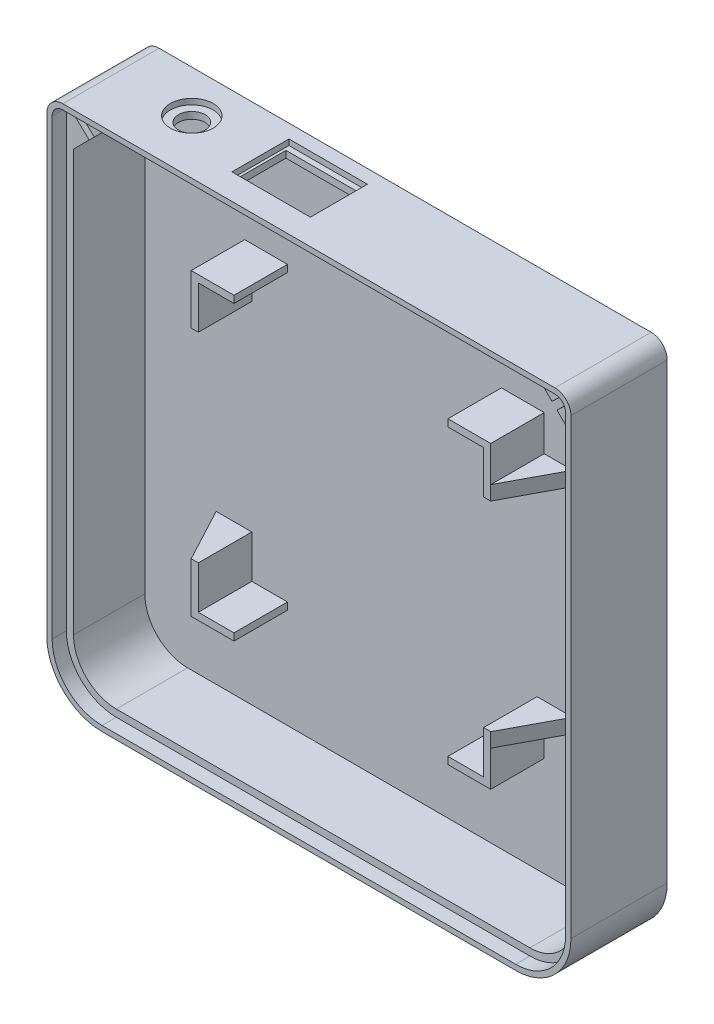
SolidWorks part; units mm, degrees
ref_plane "Front Plane" through (0, 0, 0) normal (0, 0, 1) x (1, 0, 0)
ref_plane "Top Plane" through (0, 0, 0) normal (0, 1, 0) x (1, 0, 0)
ref_plane "Right Plane" through (0, 0, 0) normal (1, 0, 0) x (0, 0, -1)
sketch "Sketch1" plane through (0, 0, 0) normal (0, 0, 1) x (1, 0, 0)
  line L1 (58, -72) -> (-58, -72)
  line L2 (72, -58) -> (72, 72)
  line L3 (72, 72) -> (-72, 72)
  line L4 (-72, -58) -> (-72, 72)
  line L5 (72, -72) -> (-72, 72) construction
  line L6 (72, 72) -> (-72, -72) construction
  arc A0 (58, -72) -> (72, -58) centre (58, -58) ccw
  arc A1 (-58, -72) -> (-72, -58) centre (-58, -58) cw
  point P0 (0, 0)
  dimension "D3" = 14
  dimension "D1" = 144
  dimension "D2" = 144
extrude "Boss-Extrude1" add sketch "Sketch1" along normal blind 3
sketch "Sketch2" plane through (0, 0, 3) normal (0, 0, 1) x (1, 0, 0)
  line L4 (-70, 70) -> (-70, -58)
  line L5 (-58, -70) -> (58, -70)
  line L6 (70, -58) -> (70, 70)
  line L7 (70, 70) -> (-70, 70)
  line L8 (-72, 72) -> (-72, -58)
  line L9 (-58, -72) -> (58, -72)
  line L10 (72, -58) -> (72, 72)
  line L11 (72, 72) -> (-72, 72)
  line L12 (-72, 72) -> (-72, -58)
  line L13 (-58, -72) -> (58, -72)
  line L14 (72, -58) -> (72, 72)
  line L15 (72, 72) -> (-72, 72)
  arc A2 (-70, -58) -> (-58, -70) centre (-58, -58) ccw
  arc A3 (58, -70) -> (70, -58) centre (58, -58) ccw
  arc A4 (-72, -58) -> (-58, -72) centre (-58, -58) ccw
  arc A5 (58, -72) -> (72, -58) centre (58, -58) ccw
  arc A6 (-72, -58) -> (-58, -72) centre (-58, -58) ccw
  arc A7 (58, -72) -> (72, -58) centre (58, -58) ccw
  dimension "D1" = 0
  dimension "D2" = 2
extrude "Boss-Extrude2" add sketch "Sketch2" along normal blind 20
chamfer "Chamfer1" distance 10 angle 45 2 edges at (70, 70, 13) (-70, 70, 13)
sketch "Sketch3" plane through (0, 0, 3) normal (0, 0, 1) x (1, 0, 0)
  line L0 (-42, -42) -> (-42, 42)
  line L1 (-40, -40) -> (40, -40)
  line L2 (-40, -40) -> (-40, 40)
  line L3 (-40, 40) -> (40, 40)
  line L4 (40, -40) -> (40, 40)
  line L5 (-40, -40) -> (40, 40) construction
  line L6 (-40, 40) -> (40, -40) construction
  line L7 (-42, 42) -> (42, 42)
  line L8 (42, -42) -> (42, 42)
  line L9 (-42, -42) -> (42, -42)
  point P0 (0, 0)
  dimension "D1" = 80
  dimension "D2" = 80
  dimension "D3" = 2
extrude "Boss-Extrude3" add sketch "Sketch3" along normal blind 15
ref_plane "Plane1" through (0, 20, 0) normal (0, 1, 0) x (1, 0, 0)
ref_plane "Plane2" through (0, -20, 0) normal (0, 1, 0) x (1, 0, 0)
sketch "Sketch6" plane through (0, -42, 0) normal (0, -1, 0) x (1, 0, 0)
  line L0 (-42, 3) -> (-50, 3)
  line L1 (-50, 3) -> (-42, 18)
  line L2 (-42, 18) -> (-42, 3)
  line L3 (0, 0) -> (0, 10.5) construction
  line L4 (42, 18) -> (42, 3)
  line L5 (50, 3) -> (42, 18)
  line L6 (42, 3) -> (50, 3)
extrude "Boss-Extrude4" add sketch "Sketch6" against normal blind 84
sketch "Sketch7" plane through (0, 0, 3) normal (0, 0, 1) x (1, 0, 0)
  line L0 (-50, 42) -> (-50, -42) construction
  line L1 (-50, 32) -> (-42, 32)
  line L2 (-50, 32) -> (-50, 42)
  line L3 (-50, 42) -> (-42, 42)
  line L4 (-42, 32) -> (-42, 42)
  line L5 (-42, 42) -> (-42, -42) construction
  line L6 (-42, 28) -> (-50, 28)
  line L7 (-42, 28) -> (-42, -28)
  line L8 (-42, -28) -> (-50, -28)
  line L9 (-50, 28) -> (-50, -28)
  line L10 (-50, -42) -> (50, -42) construction
  line L11 (-50, -32) -> (-42, -32)
  line L12 (-50, -32) -> (-50, -42)
  line L13 (-50, -42) -> (-42, -42)
  line L14 (-42, -32) -> (-42, -42)
  line L15 (-42, -42) -> (-50, -42) construction
  line L16 (0, 0) -> (0, 12.3491) construction
  line L17 (42, -32) -> (42, -42)
  line L18 (50, -42) -> (42, -42)
  line L19 (50, -32) -> (50, -42)
  line L20 (50, -32) -> (42, -32)
  line L21 (50, 28) -> (50, -28)
  line L22 (42, -28) -> (50, -28)
  line L23 (42, 28) -> (42, -28)
  line L24 (42, 28) -> (50, 28)
  line L25 (42, 32) -> (42, 42)
  line L26 (50, 42) -> (42, 42)
  line L27 (50, 32) -> (50, 42)
  line L28 (50, 32) -> (42, 32)
  line L29 (50, 42) -> (-50, 42) construction
  line L30 (-30, 42) -> (30, 42)
  line L31 (-30, 42) -> (-30, -42)
  line L32 (-30, -42) -> (30, -42)
  line L33 (30, 42) -> (30, -42)
  line L34 (-40, 40) -> (-40, -40) construction
  dimension "D1" = 10
  dimension "D2" = 4
  dimension "D3" = 4
  dimension "D4" = 10
  dimension "D5" = 60
  dimension "D6" = 10
extrude "Cut-Extrude1" cut sketch "Sketch7" along normal blind 72
fillet "Fillet1" radius 3 2 edges at (-72, 72, 11.5) (72, 72, 11.5)
sketch "Sketch9" plane through (0, 0, 0) normal (0, 0, -1) x (-1, 0, 0)
  line L1 (-72, -58) -> (72, -58) construction
  line L6 (72, -58) -> (72, 69)
  line L7 (69, 72) -> (-69, 72)
  line L8 (-72, 69) -> (-72, -58)
  line L9 (-58, -72) -> (58, -72)
  line L10 (73.5, -58) -> (73.5, 69)
  line L11 (69, 73.5) -> (-69, 73.5)
  line L12 (-73.5, 69) -> (-73.5, -58)
  line L13 (-58, -73.5) -> (58, -73.5)
  line L14 (73.5, -58) -> (73.5, 69)
  line L15 (69, 73.5) -> (-69, 73.5)
  line L16 (-73.5, 69) -> (-73.5, -58)
  line L17 (-58, -73.5) -> (58, -73.5)
  arc A4 (72, 69) -> (69, 72) centre (69, 69) ccw
  arc A5 (-69, 72) -> (-72, 69) centre (-69, 69) ccw
  arc A6 (-72, -58) -> (-58, -72) centre (-58, -58) ccw
  arc A7 (58, -72) -> (72, -58) centre (58, -58) ccw
  arc A8 (73.5, 69) -> (69, 73.5) centre (69, 69) ccw
  arc A9 (-69, 73.5) -> (-73.5, 69) centre (-69, 69) ccw
  arc A10 (-73.5, -58) -> (-58, -73.5) centre (-58, -58) ccw
  arc A11 (58, -73.5) -> (73.5, -58) centre (58, -58) ccw
  arc A12 (73.5, 69) -> (69, 73.5) centre (69, 69) ccw
  arc A13 (-69, 73.5) -> (-73.5, 69) centre (-69, 69) ccw
  arc A14 (-73.5, -58) -> (-58, -73.5) centre (-58, -58) ccw
  arc A15 (58, -73.5) -> (73.5, -58) centre (58, -58) ccw
  dimension "D1" = 1.5
  dimension "D2" = 1.5
extrude "Boss-Extrude5" add sketch "Sketch9" against normal blind 27
sketch "Sketch10" plane through (0, 70, 0) normal (0, -1, 0) x (1, 0, 0)
  line L0 (-58, 23) -> (-58, 3) construction
  circle A0 centre (-48, 11.8327) radius 3.75
  dimension "D1" = 10
extrude "Cut-Extrude2" cut sketch "Sketch10" against normal blind 26
sketch "Sketch11" plane through (0, 0, 23) normal (0, 0, 1) x (1, 0, 0)
  line L0 (-69.6886, 68.2749) -> (-65.604, 64.396)
  line L1 (-70, 60) -> (-60, 70) construction
  line L2 (-68.2424, 69.6527) -> (-64.1789, 65.8211)
  line L3 (-64.1789, 65.8211) -> (-65.604, 64.396)
  line L4 (0, 0) -> (0, 11.8359) construction
  line L5 (64.1789, 65.8211) -> (65.604, 64.396)
  line L6 (68.2424, 69.6527) -> (64.1789, 65.8211)
  line L7 (69.6886, 68.2749) -> (65.604, 64.396)
  arc A0 (-68.2424, 69.6527) -> (-69.6886, 68.2749) centre (-69, 69) ccw
  arc A1 (68.2424, 69.6527) -> (69.6886, 68.2749) centre (69, 69) cw
extrude "Cut-Extrude3" cut sketch "Sketch11" against normal blind 5
sketch "Sketch12" plane through (0, 0, 18) normal (0, 0, 1) x (1, 0, 0)
  line L0 (0, 0) -> (0, 13.3943) construction
  circle A0 centre (-69, 69) radius 1
  circle A1 centre (69, 69) radius 1
  point P8 (0, 0)
extrude "Cut-Extrude4" cut sketch "Sketch12" against normal blind 33 contours A1 | A0
sketch "Sketch14" plane through (0, 73.5, 0) normal (0, 1, 0) x (1, 0, 0)
  circle A0 centre (-48, -11.8327) radius 6
extrude "Cut-Extrude5" cut sketch "Sketch14" against normal blind 1.6
sketch "Sketch15" plane through (0, 73.5, 0) normal (0, 1, 0) x (1, 0, 0)
  line L1 (-28, -18.2327) -> (-7.5, -18.2327)
  line L2 (-28, -18.2327) -> (-28, -5.4327)
  line L3 (-28, -5.4327) -> (-7.5, -5.4327)
  line L4 (-7.5, -18.2327) -> (-7.5, -5.4327)
  line L5 (-28, -18.2327) -> (-7.5, -5.4327) construction
  line L6 (-28, -5.4327) -> (-7.5, -18.2327) construction
  circle A0 centre (-48, -11.8327) radius 6 construction
  point P0 (-17.75, -11.8327)
  dimension "D3" = 0
  dimension "D1" = 12.8
  dimension "D2" = 20.5
  dimension "D4" = 20
extrude "Cut-Extrude6" cut sketch "Sketch15" against normal blind 9.6
sketch "Sketch16" plane through (0, 73.5, 0) normal (0, 1, 0) x (1, 0, 0)
  line L1 (-6.75, -19.8327) -> (-28.75, -19.8327)
  line L2 (-6.75, -19.8327) -> (-6.75, -3.8327)
  line L3 (-6.75, -3.8327) -> (-28.75, -3.8327)
  line L4 (-28.75, -19.8327) -> (-28.75, -3.8327)
  line L5 (-6.75, -19.8327) -> (-28.75, -3.8327) construction
  line L6 (-6.75, -3.8327) -> (-28.75, -19.8327) construction
  point P0 (-17.75, -11.8327)
extrude "Cut-Extrude7" cut sketch "Sketch16" against normal blind 1.6
sketch "Sketch18" plane through (0, 0, 18) normal (0, 0, 1) x (1, 0, 0)
  line L1 (-42, 28) -> (42, 28)
  line L2 (-42, 28) -> (-42, -28)
  line L3 (-42, -28) -> (42, -28)
  line L4 (42, 28) -> (42, -28)
extrude "Cut-Extrude8" cut sketch "Sketch18" against normal blind 15
